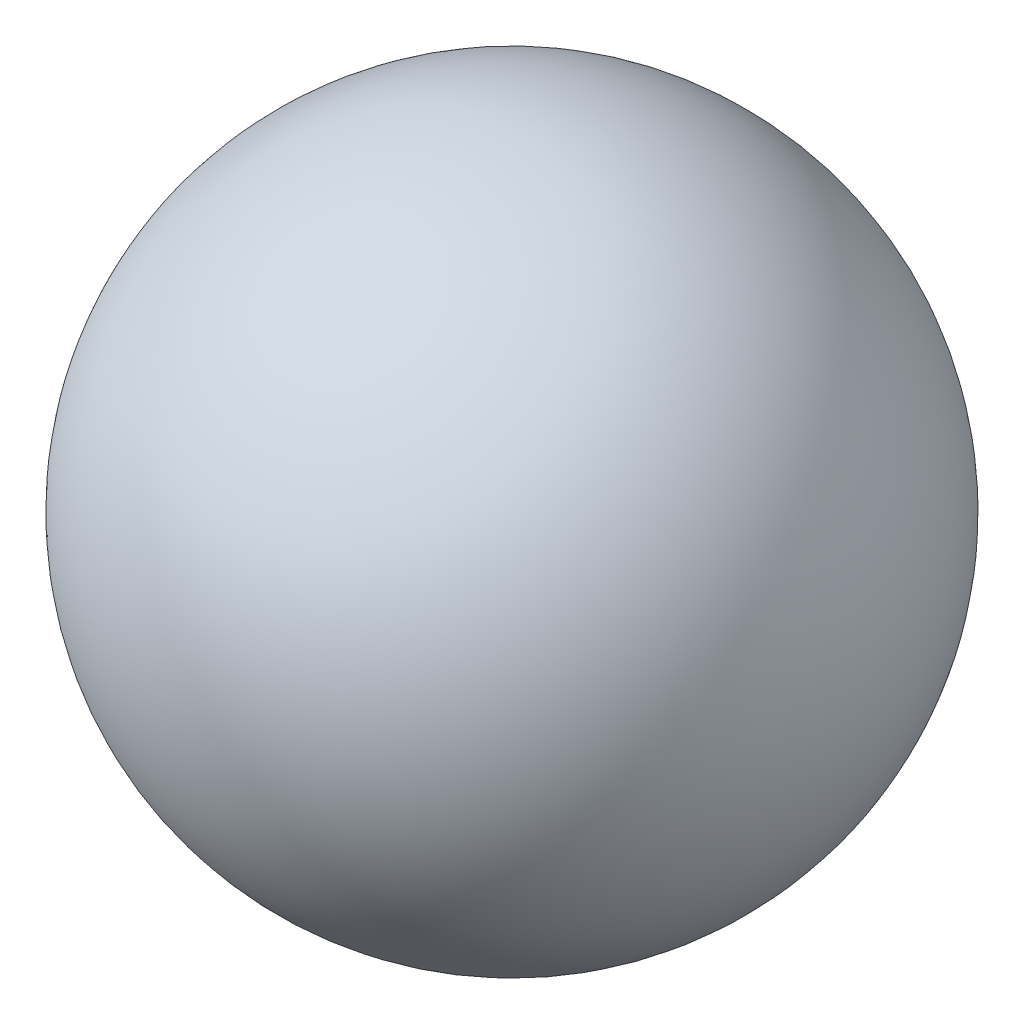
SolidWorks part; units mm, degrees
ref_plane "Front Plane" through (0, 0, 0) normal (0, 0, 1) x (1, 0, 0)
ref_plane "Top Plane" through (0, 0, 0) normal (0, 1, 0) x (1, 0, 0)
ref_plane "Right Plane" through (0, 0, 0) normal (1, 0, 0) x (0, 0, -1)
sketch "Sketch2" plane through (0, 0, 0) normal (0, 0, 1) x (1, 0, 0)
  line L0 (-12, 0) -> (12, 0)
  line L1 (-12, 0) -> (12, 0) construction
  arc A0 (12, 0) -> (-12, 0) centre (0, 0) cw
  point P4 (0, 0)
  dimension "D1" = 24
revolve "Revolve1" add sketch "Sketch2" angle 360 about L1
